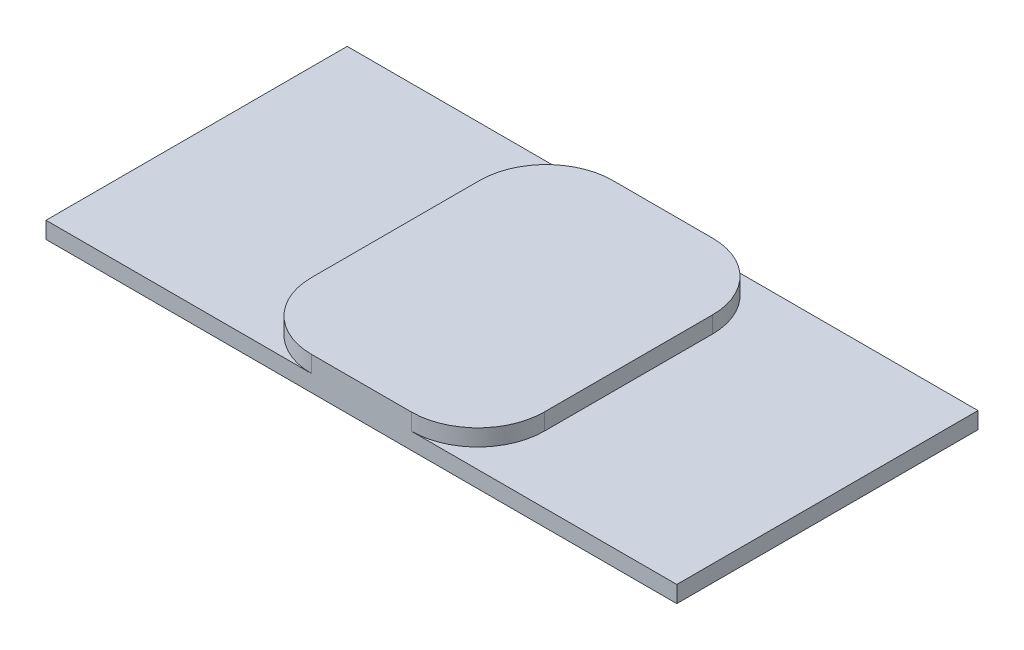
SolidWorks part; units mm, degrees
ref_plane "Front Plane" through (0, 0, 0) normal (0, 0, 1) x (1, 0, 0)
ref_plane "Top Plane" through (0, 0, 0) normal (0, 1, 0) x (1, 0, 0)
ref_plane "Right Plane" through (0, 0, 0) normal (1, 0, 0) x (0, 0, -1)
sketch "Sketch1" plane through (0, 0, 0) normal (0, 1, 0) x (1, 0, 0)
  line L1 (-120.425, 57.5) -> (120.425, 57.5)
  line L2 (-120.425, 57.5) -> (-120.425, -57.5)
  line L3 (-120.425, -57.5) -> (120.425, -57.5)
  line L4 (120.425, 57.5) -> (120.425, -57.5)
  line L5 (-120.425, 57.5) -> (120.425, -57.5) construction
  line L6 (-120.425, -57.5) -> (120.425, 57.5) construction
  point P0 (0, 0)
  dimension "D1" = 115
  dimension "D2" = 240.85
extrude "Boss-Extrude1" add sketch "Sketch1" along normal blind 6.35
sketch "Sketch2" plane through (0, 6.35, 0) normal (0, 1, 0) x (1, 0, 0)
  line L0 (-120.425, -57.5) -> (120.425, -57.5) construction
  line L1 (-44.45, 57.5) -> (44.45, 57.5)
  line L2 (-44.45, 57.5) -> (-44.45, -57.5)
  line L3 (-44.45, -57.5) -> (44.45, -57.5)
  line L4 (44.45, 57.5) -> (44.45, -57.5)
  line L5 (-44.45, 57.5) -> (44.45, -57.5) construction
  line L6 (-44.45, -57.5) -> (44.45, 57.5) construction
  point P0 (0, 0)
  dimension "D1" = 88.9
extrude "Boss-Extrude2" add sketch "Sketch2" along normal blind 6.35
fillet "Fillet1" radius 25.4 4 edges at (-44.45, 9.525, -57.5) (44.45, 9.525, -57.5) (44.45, 9.525, 57.5) (-44.45, 9.525, 57.5)
